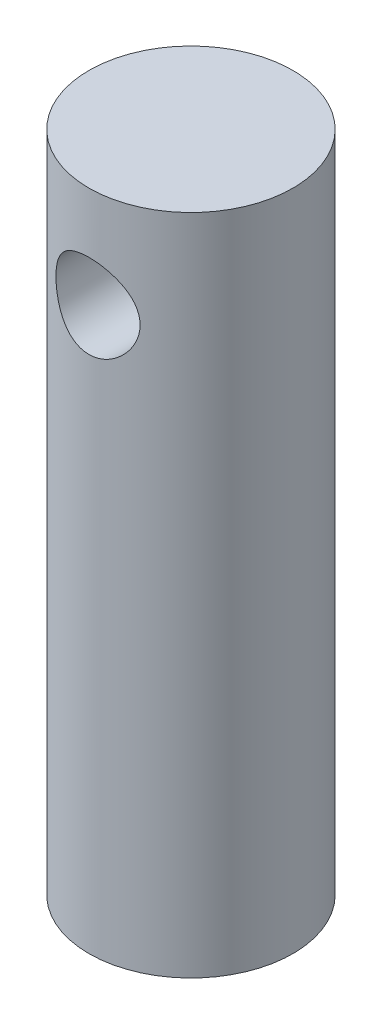
SolidWorks part; units mm, degrees
ref_plane "Front Plane" through (0, 0, 0) normal (0, 0, 1) x (1, 0, 0)
ref_plane "Top Plane" through (0, 0, 0) normal (0, 1, 0) x (1, 0, 0)
ref_plane "Right Plane" through (0, 0, 0) normal (1, 0, 0) x (0, 0, -1)
sketch "Sketch1" plane through (0, 0, 0) normal (0, 1, 0) x (1, 0, 0)
  circle A0 centre (0, 0) radius 4
  dimension "D1" = 8
extrude "Boss-Extrude1" add sketch "Sketch1" along normal blind 26
sketch "Sketch2" plane through (0, 0, 0) normal (0, 0, 1) x (1, 0, 0)
  circle A0 centre (0, 22) radius 1.65
  dimension "D1" = 3.3
  dimension "D2" = 22
extrude "Cut-Extrude1" cut sketch "Sketch2" against normal through all both and the other way through all
